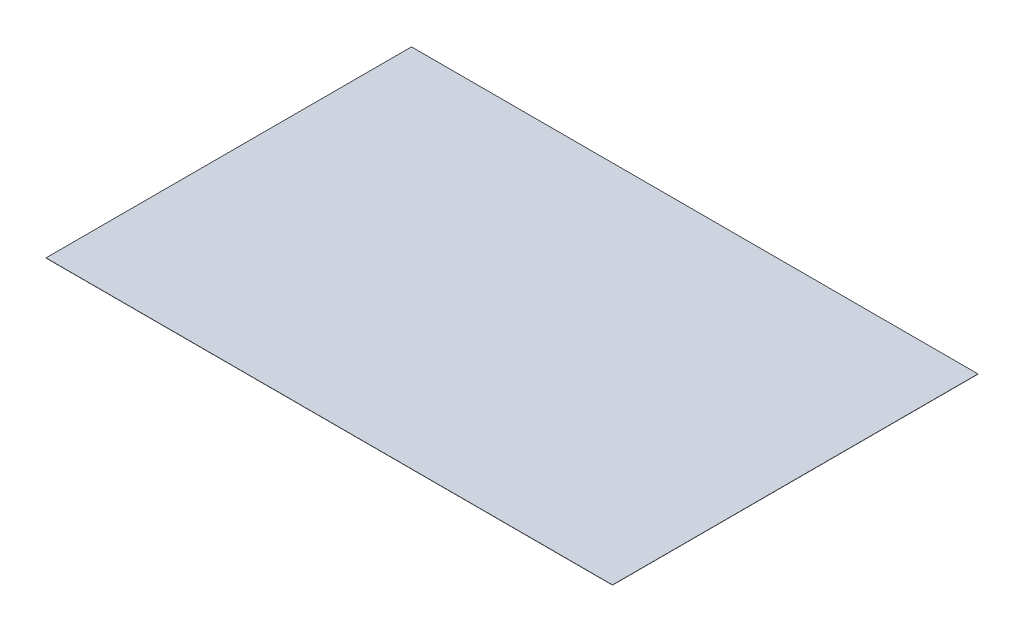
SolidWorks part; units mm, degrees
ref_plane "Спереди" through (0, 0, 0) normal (0, 0, 1) x (1, 0, 0)
ref_plane "Сверху" through (0, 0, 0) normal (0, 1, 0) x (1, 0, 0)
ref_plane "Справа" through (0, 0, 0) normal (1, 0, 0) x (0, 0, -1)
other "Configuration Table"
sketch "Эскиз1" plane through (0, 0, 0) normal (0, 1, 0) x (1, 0, 0)
  line L1 (1550, 1000) -> (-1550, 1000)
  line L2 (1550, 1000) -> (1550, -1000)
  line L3 (1550, -1000) -> (-1550, -1000)
  line L4 (-1550, 1000) -> (-1550, -1000)
  line L5 (1550, 1000) -> (-1550, -1000) construction
  line L6 (1550, -1000) -> (-1550, 1000) construction
  point P0 (0, 0)
extrude "Бобышка-Вытянуть1" add sketch "Эскиз1" along normal blind 1
